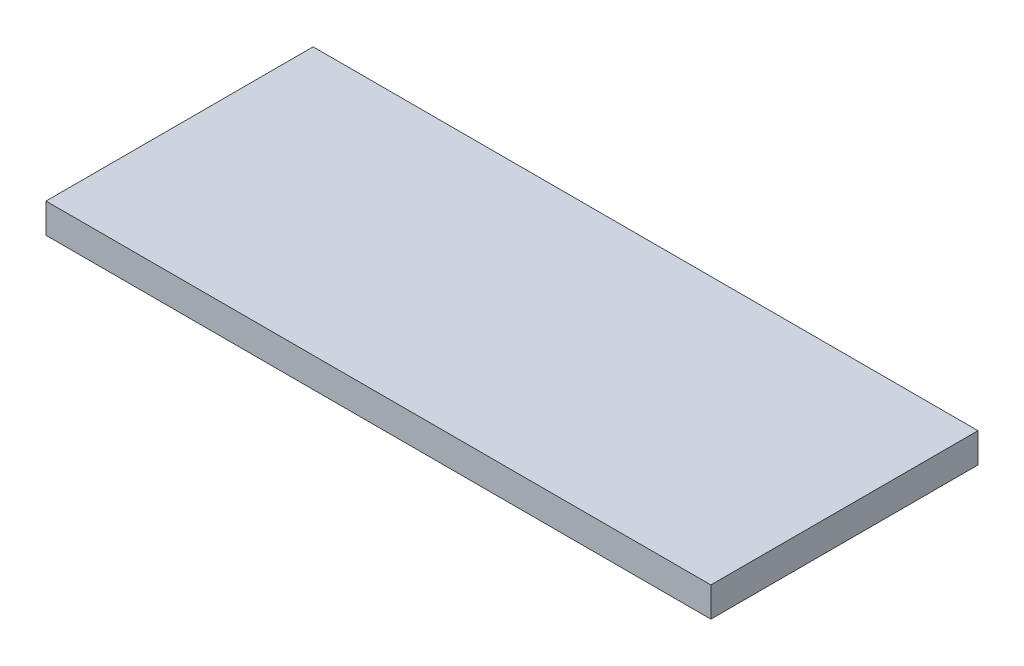
SolidWorks part; units mm, degrees
ref_plane "前视基准面" through (0, 0, 0) normal (0, 0, 1) x (1, 0, 0)
ref_plane "上视基准面" through (0, 0, 0) normal (0, 1, 0) x (1, 0, 0)
ref_plane "右视基准面" through (0, 0, 0) normal (1, 0, 0) x (0, 0, -1)
sketch "草图2" plane through (0, 0, 0) normal (0, 1, 0) x (1, 0, 0)
  line L1 (112, 45) -> (-112, 45)
  line L2 (112, 45) -> (112, -45)
  line L3 (112, -45) -> (-112, -45)
  line L4 (-112, 45) -> (-112, -45)
  line L5 (112, 45) -> (-112, -45) construction
  line L6 (112, -45) -> (-112, 45) construction
  point P0 (0, 0)
  dimension "D1" = 90
  dimension "D2" = 224
extrude "凸台-拉伸1" add sketch "草图2" along normal blind 10
sketch "草图3" plane through (0, 10, 0) normal (0, 1, 0) x (1, 0, 0)
  line L0 (0, 45) -> (0, -45) construction
  line L1 (112, 45) -> (-112, 45) construction
  line L2 (-112, -45) -> (112, -45) construction
